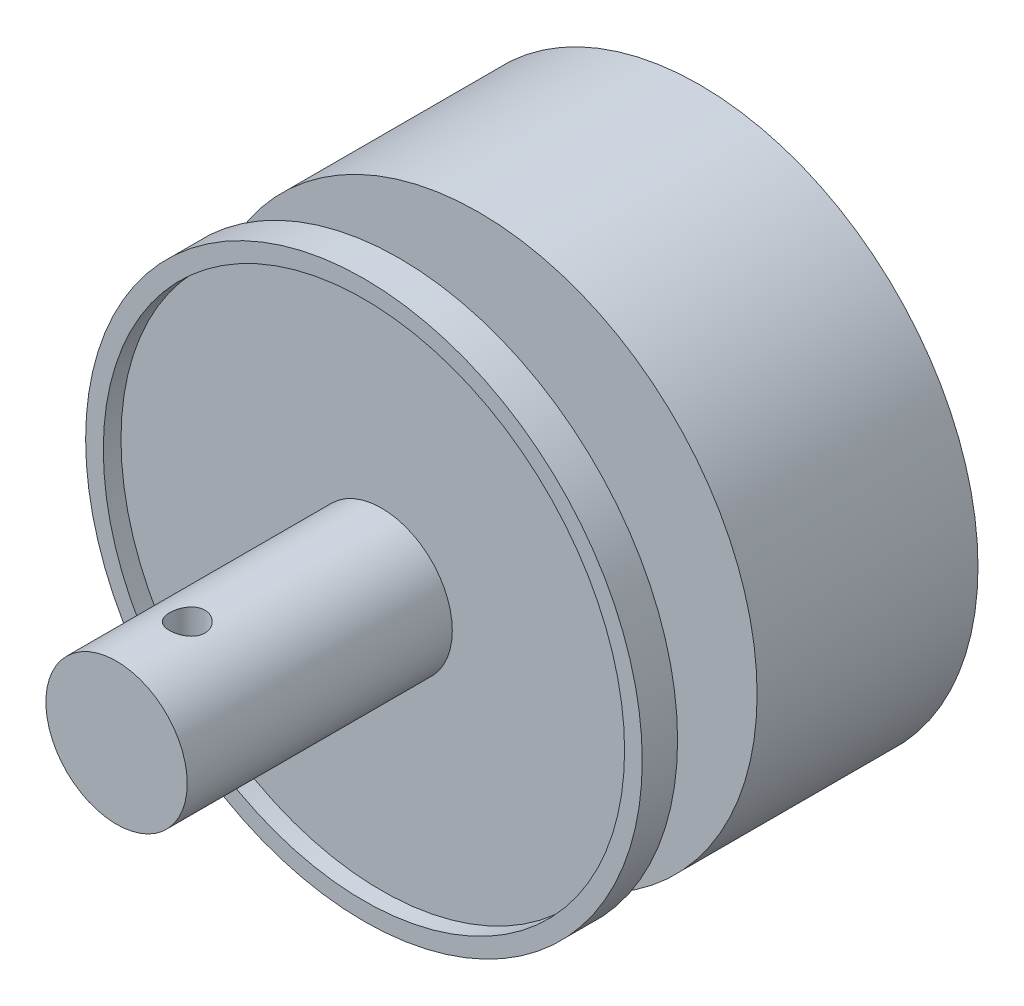
SolidWorks part; units mm, degrees
ref_plane "Front" through (0, 0, 0) normal (0, 0, 1) x (1, 0, 0)
ref_plane "Top" through (0, 0, 0) normal (0, 1, 0) x (1, 0, 0)
ref_plane "Right" through (0, 0, 0) normal (1, 0, 0) x (0, 0, -1)
sketch "草图1" plane through (0, 0, 0) normal (0, 0, 1) x (1, 0, 0)
  circle A0 centre (0, 0) radius 31.5
  dimension "D1" = 63
extrude "凸台-拉伸1" add sketch "草图1" along normal blind 25
sketch "草图2" plane through (0, 0, 25) normal (0, 0, 1) x (1, 0, 0)
  circle A0 centre (0, 0) radius 5
  dimension "D1" = 10
extrude "凸台-拉伸2" add sketch "草图2" along normal blind 9
sketch "草图3" plane through (0, 0, 34) normal (0, 0, 1) x (1, 0, 0)
  circle A0 centre (0, 0) radius 31.5
extrude "凸台-拉伸3" add sketch "草图3" along normal blind 4
sketch "草图4" plane through (0, 0, 38) normal (0, 0, 1) x (1, 0, 0)
  circle A0 centre (0, 0) radius 29.5
  dimension "D1" = 59
extrude "切除-拉伸1" cut sketch "草图4" against normal blind 2
sketch "草图5" plane through (0, 0, 36) normal (0, 0, 1) x (1, 0, 0)
  circle A0 centre (0, 0) radius 8
extrude "凸台-拉伸4" add sketch "草图5" along normal blind 30
sketch "草图6" plane through (0, 0, 0) normal (0, 1, 0) x (1, 0, 0)
  line L0 (0, 10.406) -> (0, -113.9144) construction
  line L1 (-8, -66) -> (8, -66) construction
  circle A0 centre (0, -58) radius 2
  dimension "D1" = 4
  dimension "D2" = 8
extrude "切除-拉伸2" cut sketch "草图6" against normal mid plane 40
